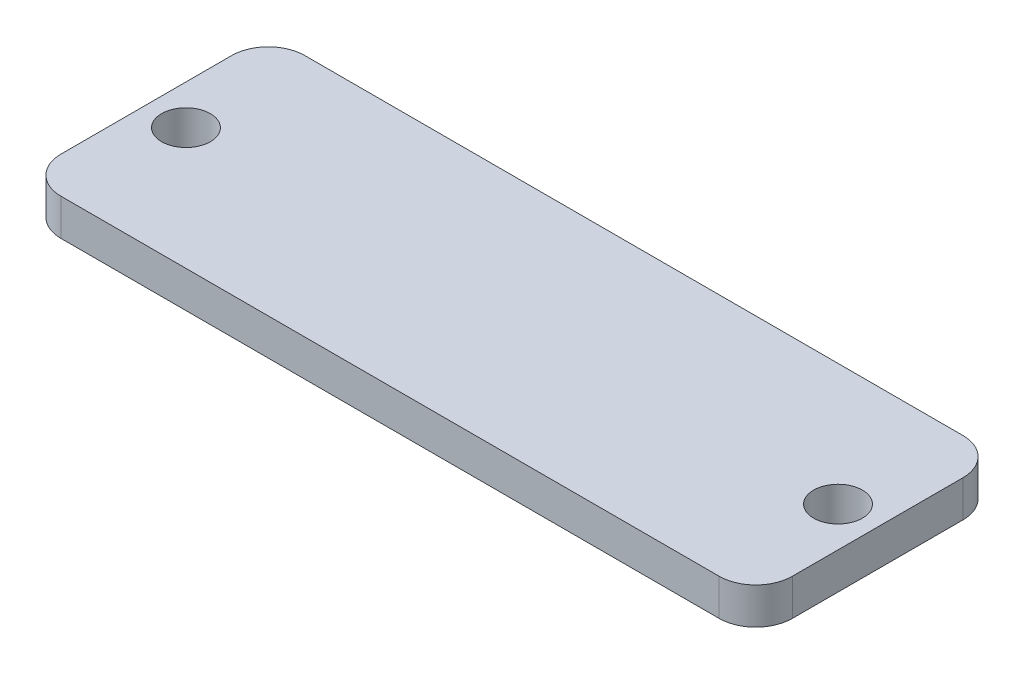
SolidWorks part; units mm, degrees
ref_plane "Спереди" through (0, 0, 0) normal (0, 0, 1) x (1, 0, 0)
ref_plane "Сверху" through (0, 0, 0) normal (0, 1, 0) x (1, 0, 0)
ref_plane "Справа" through (0, 0, 0) normal (1, 0, 0) x (0, 0, -1)
sketch "Эскиз1" plane through (0, 0, 0) normal (0, 1, 0) x (1, 0, 0)
  line L1 (-30, -10) -> (30, -10)
  line L2 (-30, -10) -> (-30, 10)
  line L3 (-30, 10) -> (30, 10)
  line L4 (30, -10) -> (30, 10)
  line L5 (0, 10) -> (0, -10) construction
  line L6 (-30, 0) -> (30, 0) construction
  point P0 (0, 0)
  dimension "D1" = 60
  dimension "D2" = 20
extrude "Бобышка-Вытянуть1" add sketch "Эскиз1" along normal blind 3
fillet "Скругление1" radius 3 4 edges at (-30, 1.5, -10) (30, 1.5, -10) (30, 1.5, 10) (-30, 1.5, 10)
sketch "Эскиз2" plane through (0, 3, 0) normal (0, 1, 0) x (1, 0, 0)
  line L0 (0, 14.2359) -> (0, 0) construction
  line L1 (0, 0) -> (32.5327, 0) construction
  circle A0 centre (26.75, 0) radius 2
  circle A1 centre (-26.75, 0) radius 2
  dimension "D1" = 26.75
extrude "Вырез-Вытянуть1" cut sketch "Эскиз2" against normal blind 3
